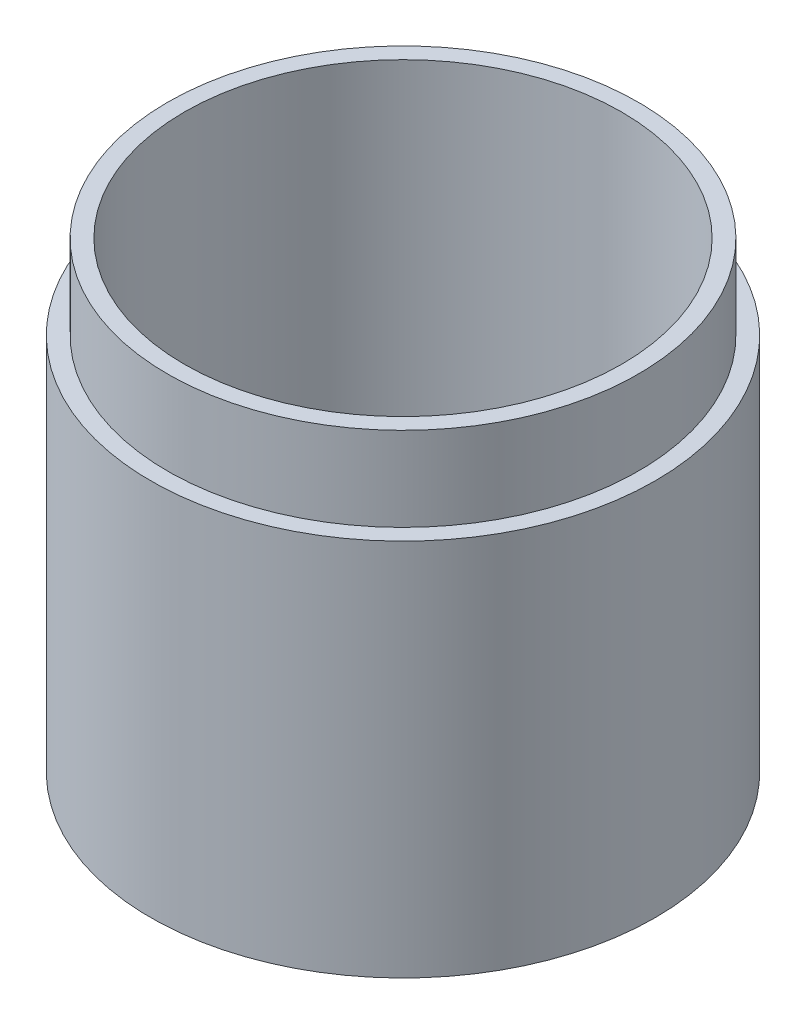
SolidWorks part; units mm, degrees
ref_plane "Front Plane" through (0, 0, 0) normal (0, 0, 1) x (1, 0, 0)
ref_plane "Top Plane" through (0, 0, 0) normal (0, 1, 0) x (1, 0, 0)
ref_plane "Right Plane" through (0, 0, 0) normal (1, 0, 0) x (0, 0, -1)
sketch "Sketch1" plane through (0, 0, 0) normal (0, 0, 1) x (1, 0, 0)
  line L0 (0, 0) -> (38.1, 0)
  line L1 (38.1, 0) -> (38.1, 57.15)
  line L2 (38.1, 57.15) -> (35.56, 57.15)
  line L3 (35.56, 57.15) -> (35.56, 69.85)
  line L4 (35.56, 69.85) -> (33.02, 69.85)
  line L5 (33.02, 69.85) -> (33.02, 5.08)
  line L6 (33.02, 5.08) -> (0, 5.08)
  line L7 (0, 5.08) -> (0, 0)
  line L8 (0, 5.08) -> (0, 63.5914) construction
  dimension "D1" = 2.54
  dimension "D2" = 5.08
  dimension "D3" = 5.08
  dimension "D4" = 69.85
  dimension "D5" = 12.7
  dimension "D6" = 76.2
revolve "Revolve1" add sketch "Sketch1" angle 360 about L7
